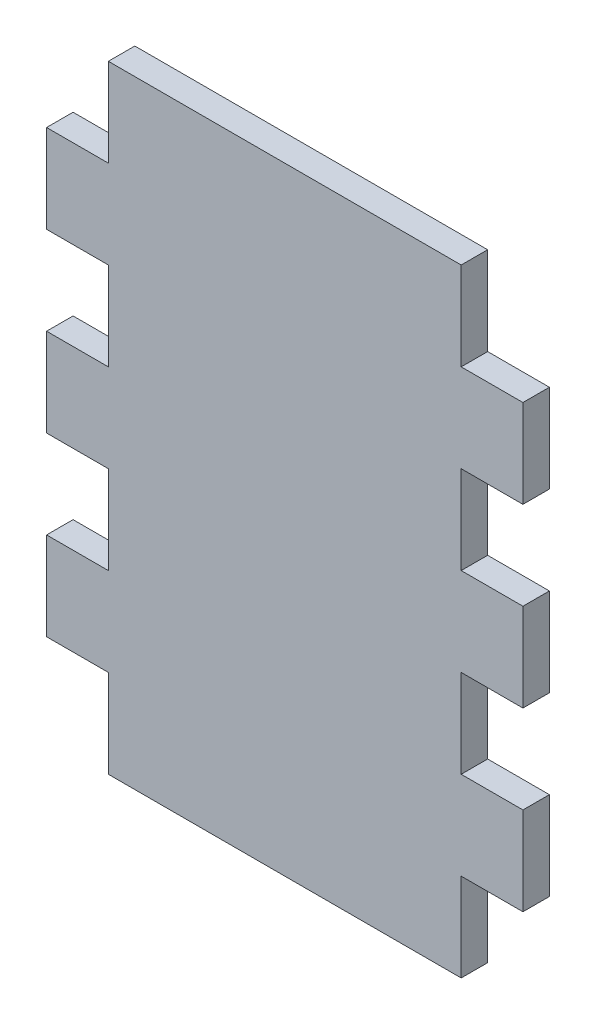
SolidWorks part; units mm, degrees
ref_plane "Plano frontal" through (0, 0, 0) normal (0, 0, 1) x (1, 0, 0)
ref_plane "Plano superior" through (0, 0, 0) normal (0, 1, 0) x (1, 0, 0)
ref_plane "Plano direito" through (0, 0, 0) normal (1, 0, 0) x (0, 0, -1)
sketch "Esboço1" plane through (0, 0, 0) normal (0, 0, 1) x (1, 0, 0)
  line L0 (0, 35) -> (0, -35)
  line L1 (-20, -35) -> (20, -35)
  line L2 (-20, -35) -> (-20, 35)
  line L3 (-20, 35) -> (20, 35)
  line L4 (20, -35) -> (20, 35)
  line L5 (-20, -35) -> (20, 35) construction
  line L6 (-20, 35) -> (20, -35) construction
  line L7 (20, 35) -> (43.8883, 35)
  line L8 (-20, -25) -> (-27, -25)
  line L9 (20, 25) -> (27, 25)
  line L10 (20, 25) -> (20, 15)
  line L11 (20, 15) -> (27, 15)
  line L12 (27, 25) -> (27, 15)
  line L13 (20, 5) -> (27, 5)
  line L14 (20, 5) -> (20, -5)
  line L15 (20, -5) -> (27, -5)
  line L16 (27, 5) -> (27, -5)
  line L17 (20, -15) -> (27, -15)
  line L18 (20, -15) -> (20, -25)
  line L19 (20, -25) -> (27, -25)
  line L20 (27, -15) -> (27, -25)
  line L21 (-27, -15) -> (-27, -25)
  line L22 (-20, -15) -> (-27, -15)
  line L23 (-20, -15) -> (-20, -25)
  line L24 (-20, -5) -> (-27, -5)
  line L25 (-27, 5) -> (-27, -5)
  line L26 (-20, 5) -> (-27, 5)
  line L27 (-20, 5) -> (-20, -5)
  line L28 (-20, 15) -> (-27, 15)
  line L29 (-27, 25) -> (-27, 15)
  line L30 (-20, 25) -> (-27, 25)
  line L31 (-20, 25) -> (-20, 15)
  point P0 (0, 0)
  dimension "D1" = 70
  dimension "D2" = 40
  dimension "D3" = 10
  dimension "D4" = 7
  dimension "D5" = 10
  dimension "D6" = 10
  dimension "D7" = 10
  dimension "D8" = 7
  dimension "D9" = 7
  dimension "D10" = 10
  dimension "D11" = 10
extrude "Ressalto-extrusão1" add sketch "Esboço1" along normal blind 3 contours L2 L26 L25 L24 | L2 L22 L21 L8 | L12 L9 L4 L11 | L16 L13 L4 L15 | L20 L17 L4 L19 | L3 L2 L1 L0 | L1 L4 L3 L0 | L29 L28 L31 L30
